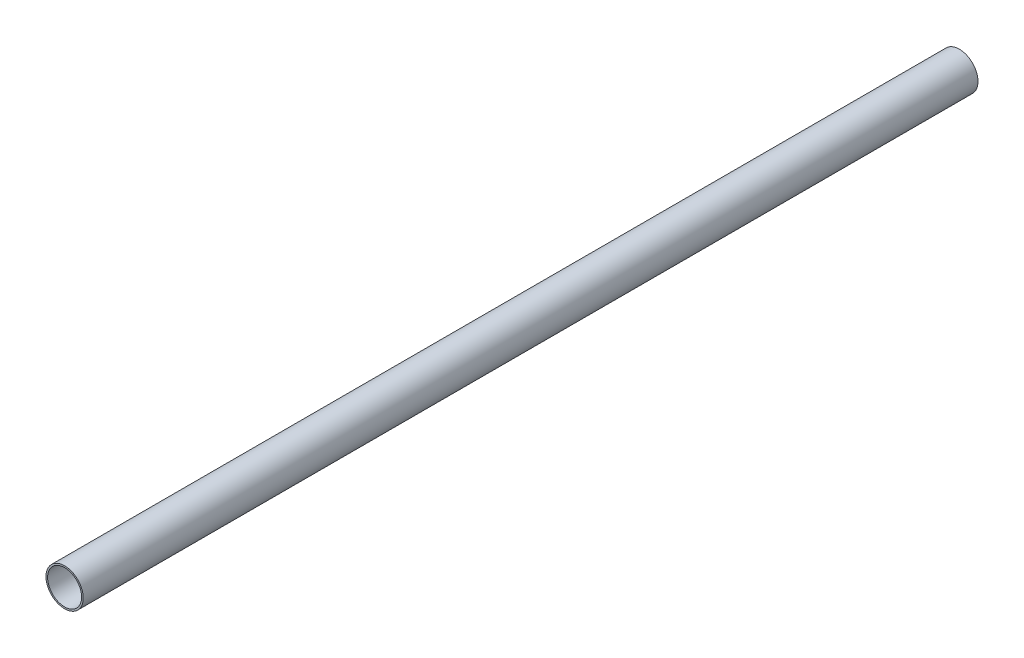
SolidWorks part; units mm, degrees
ref_plane "Front Plane" through (0, 0, 0) normal (0, 0, 1) x (1, 0, 0)
ref_plane "Top Plane" through (0, 0, 0) normal (0, 1, 0) x (1, 0, 0)
ref_plane "Right Plane" through (0, 0, 0) normal (1, 0, 0) x (0, 0, -1)
sketch "Sketch1" plane through (0, 0, 0) normal (0, 0, 1) x (1, 0, 0)
  circle A0 centre (0, 0) radius 19.05 construction
  circle A1 centre (0, 0) radius 17.399 construction
  point P3 (-19.05, 0)
  point P4 (19.05, 0)
  point P6 (-17.399, 0)
  point P7 (17.399, 0)
  dimension "OD" = 38.1
  dimension "Wall" = 1.651
  dimension "ID" = 34.798
sketch "Sketch2" plane through (0, 0, 0) normal (1, 0, 0) x (0, 0, -1)
  line L0 (457.2, 0) -> (-457.2, 0) construction
  line L2 (0, 19.05) -> (0, -19.05) construction
  line L3 (0, 19.05) -> (0, -19.05) construction
  line L4 (457.2, 19.05) -> (-457.2, 19.05) construction
  line L5 (457.2, -19.05) -> (-457.2, -19.05) construction
  line L6 (-457.2, -19.05) -> (-457.2, 19.05) construction
  line L7 (457.2, -19.05) -> (457.2, 19.05) construction
  line L8 (-419.1, -19.05) -> (-419.1, 19.05) construction
  line L9 (419.1, -19.05) -> (419.1, 19.05) construction
  point P3 (0, 0)
  point P9 (0, 19.05)
  point P11 (0, -19.05)
  point P13 (-457.2, 0)
  point P14 (457.2, 19.05)
  point P15 (-457.2, -19.05)
  point P16 (-457.2, 19.05)
  point P17 (-457.2, 0)
  point P18 (457.2, -19.05)
  point P19 (457.2, 0)
  point P22 (-419.1, 0)
  point P25 (419.1, 0)
  point P26 (-419.1, -19.05)
  point P27 (-419.1, 19.05)
  point P28 (419.1, 19.05)
  point P29 (419.1, -19.05)
  dimension "Length" = 914.4
  dimension "D1" = 38.1
sketch "Sketch3" plane through (0, 0, 0) normal (0, 0, 1) x (1, 0, 0)
  circle A0 centre (0, 0) radius 19.05 construction
  circle A1 centre (0, 0) radius 17.399 construction
  circle A2 centre (0, 0) radius 19.05
  circle A3 centre (0, 0) radius 17.399
extrude "Boss-Extrude1" add sketch "Sketch3" along normal mid plane 914.4
equation "\"D1@Sketch2\"=\"OD@Sketch1\""
equation "\"D1@Boss-Extrude1\"=\"Length@Sketch2\""
